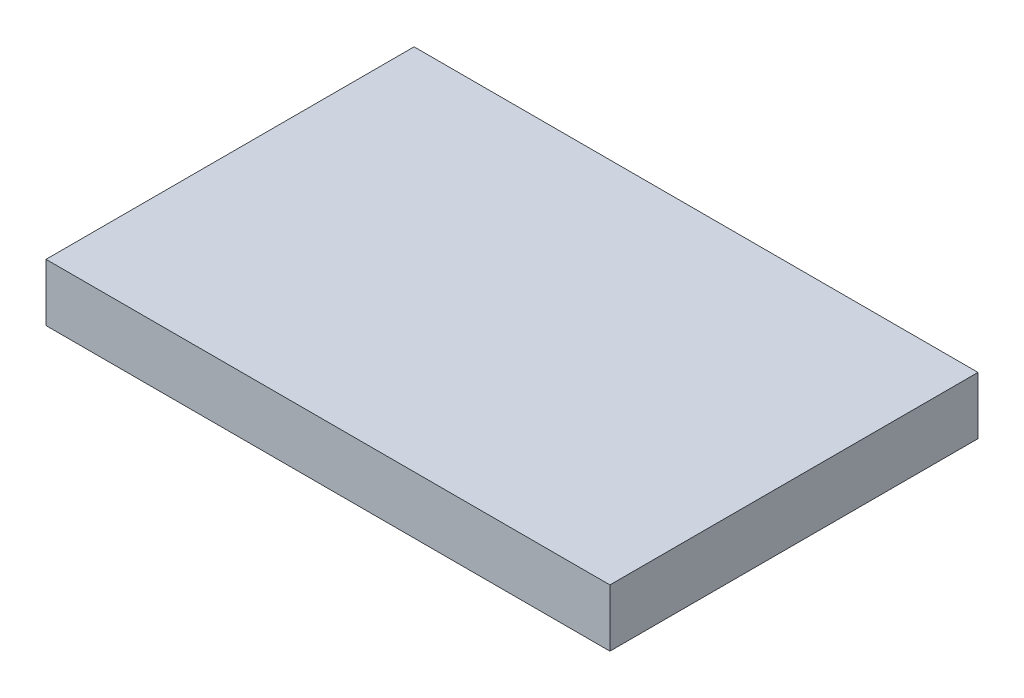
SolidWorks part; units mm, degrees
material "Monel(R) 400"
ref_plane "Front Plane" through (0, 0, 0) normal (0, 0, 1) x (1, 0, 0)
ref_plane "Top Plane" through (0, 0, 0) normal (0, 1, 0) x (1, 0, 0)
ref_plane "Right Plane" through (0, 0, 0) normal (1, 0, 0) x (0, 0, -1)
sketch "Sketch1" plane through (0, 0, 0) normal (0, 1, 0) x (1, 0, 0)
  line L1 (-41.75, 27.25) -> (41.75, 27.25)
  line L2 (-41.75, 27.25) -> (-41.75, -27.25)
  line L3 (-41.75, -27.25) -> (41.75, -27.25)
  line L4 (41.75, 27.25) -> (41.75, -27.25)
  line L5 (-41.75, 27.25) -> (41.75, -27.25) construction
  line L6 (-41.75, -27.25) -> (41.75, 27.25) construction
  point P0 (0, 0)
  dimension "D1" = 83.5
  dimension "D2" = 54.5
extrude "Boss-Extrude1" add sketch "Sketch1" along normal blind 8.5
